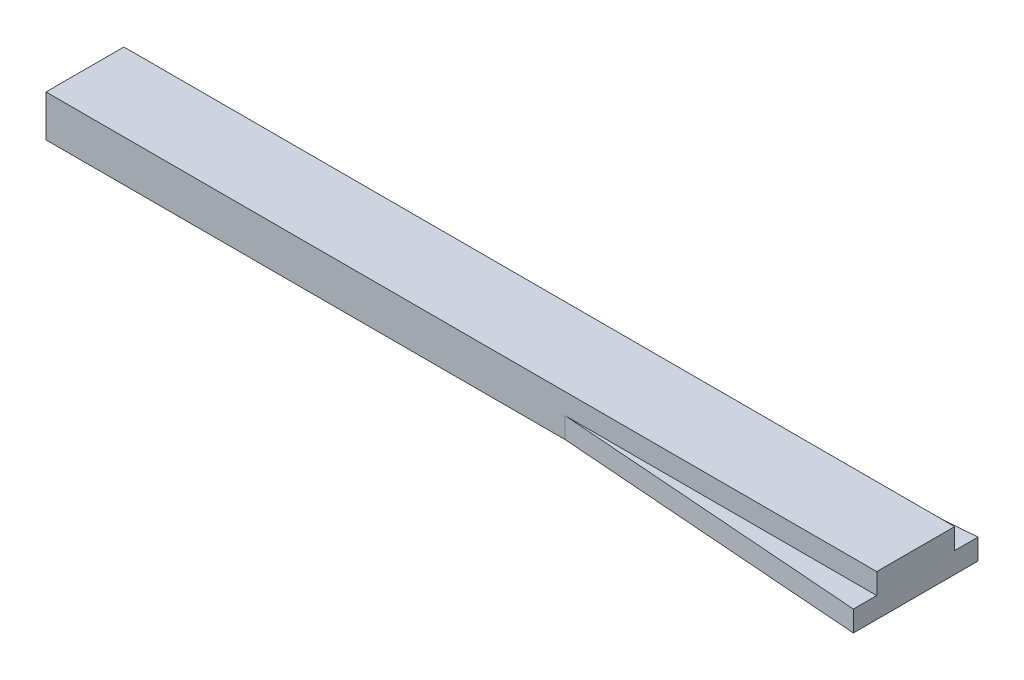
SolidWorks part; units mm, degrees
ref_plane "Front Plane" through (0, 0, 0) normal (0, 0, 1) x (1, 0, 0)
ref_plane "Top Plane" through (0, 0, 0) normal (0, 1, 0) x (1, 0, 0)
ref_plane "Right Plane" through (0, 0, 0) normal (1, 0, 0) x (0, 0, -1)
sketch "Sketch1" plane through (0, 0, 0) normal (0, 1, 0) x (1, 0, 0)
  line L1 (-125.993, 49.6167) -> (-125.993, 64.6167)
  line L2 (-125.993, 64.6167) -> (34.007, 64.6167)
  line L4 (-125.993, 49.6167) -> (34.007, 49.6167)
  line L5 (34.007, 49.6167) -> (34.007, 64.6167)
  dimension "D1" = 160
  dimension "D2" = 15
extrude "Boss-Extrude1" add sketch "Sketch1" along normal blind 4
sketch "Sketch2" plane through (0, 0, 0) normal (0, 1, 0) x (1, 0, 0)
  line L0 (-125.993, 64.6167) -> (-25.993, 64.6167)
  line L1 (34.007, 64.6167) -> (-125.993, 64.6167) construction
  line L2 (34.007, 45.1167) -> (34.007, 69.1167)
  line L3 (34.007, 49.6167) -> (34.007, 64.6167) construction
  line L4 (-25.993, 64.6167) -> (34.007, 69.1167)
  line L5 (-125.993, 64.6167) -> (-125.993, 49.6167)
  line L6 (-125.993, 64.6167) -> (-125.993, 49.6167) construction
  line L7 (-125.993, 57.1167) -> (34.007, 57.1167) construction
  line L8 (-25.993, 49.6167) -> (34.007, 45.1167)
  line L9 (-125.993, 49.6167) -> (-25.993, 49.6167)
  point P16 (34.007, 57.1167)
  point P18 (-125.993, 57.1167)
  dimension "D1" = 100
  dimension "D2" = 12
extrude "Boss-Extrude2" add sketch "Sketch2" against normal blind 4
